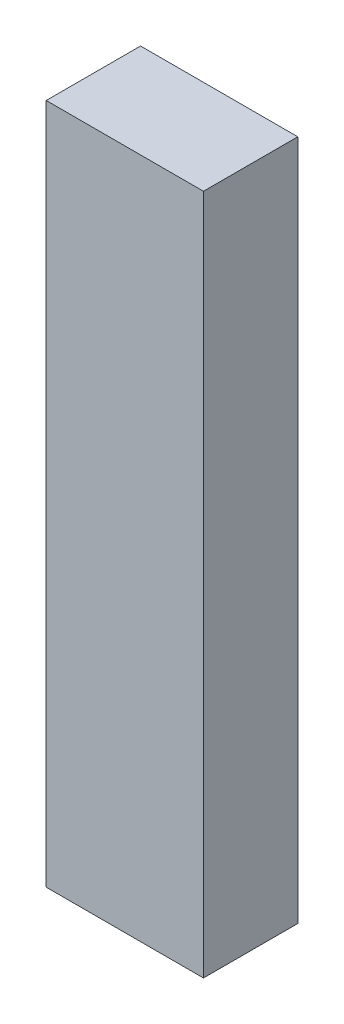
SolidWorks part; units mm, degrees
ref_plane "Plan de face" through (0, 0, 0) normal (0, 0, 1) x (1, 0, 0)
ref_plane "Plan de dessus" through (0, 0, 0) normal (0, 1, 0) x (1, 0, 0)
ref_plane "Plan de droite" through (0, 0, 0) normal (1, 0, 0) x (0, 0, -1)
sketch "Esquisse1" plane through (0, 0, 0) normal (0, 0, 1) x (1, 0, 0)
  line L1 (12.2769, 56.5293) -> (27.2769, 56.5293)
  line L2 (12.2769, 56.5293) -> (12.2769, -8.4707)
  line L3 (12.2769, -8.4707) -> (27.2769, -8.4707)
  line L4 (27.2769, 56.5293) -> (27.2769, -8.4707)
  dimension "D1" = 65
  dimension "D2" = 15
extrude "Extrusion1" add sketch "Esquisse1" along normal blind 9
